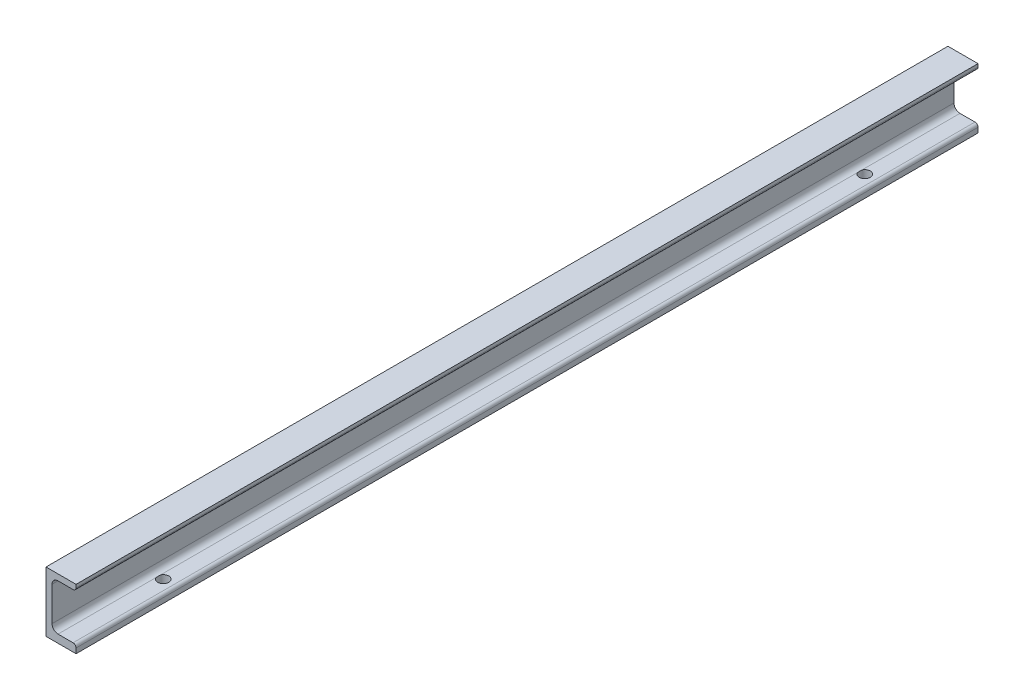
SolidWorks part; units mm, degrees
material "ASTM A36 Steel"
ref_plane "Front Plane" through (0, 0, 0) normal (0, 0, 1) x (1, 0, 0)
ref_plane "Top Plane" through (0, 0, 0) normal (0, 1, 0) x (1, 0, 0)
ref_plane "Right Plane" through (0, 0, 0) normal (1, 0, 0) x (0, 0, -1)
sketch "Sketch1" plane through (0, 0, 0) normal (0, 0, 1) x (1, 0, 0)
  line L0 (12, 24) -> (-3, 24)
  line L1 (-15, -30) -> (15, -30)
  line L2 (-15, -30) -> (-15, 30)
  line L3 (-15, 30) -> (15, 30)
  line L4 (15, -30) -> (15, -25)
  line L5 (-15, -30) -> (15, 30) construction
  line L6 (-15, 30) -> (15, -30) construction
  line L7 (-9, 18) -> (-9, -16)
  line L8 (-3, -22) -> (12, -22)
  line L9 (15, 27) -> (15, 30)
  arc A0 (-9, -16) -> (-3, -22) centre (-3, -16) ccw
  arc A1 (-3, 24) -> (-9, 18) centre (-3, 18) ccw
  arc A2 (12, -22) -> (15, -25) centre (12, -25) cw
  arc A3 (12, 24) -> (15, 27) centre (12, 27) ccw
  point P0 (0, 0)
  point P18 (15, 24)
  dimension "D5" = 6
  dimension "D6" = 3
  dimension "D1" = 60
  dimension "D2" = 30
  dimension "D3" = 6
  dimension "D4" = 6
  dimension "D7" = 8
extrude "Boss-Extrude1" add sketch "Sketch1" along normal mid plane 900
sketch "Sketch2" plane through (0, -22, 0) normal (0, 1, 0) x (1, 0, 0)
  line L0 (12, -450) -> (-3, -450) construction
  line L1 (15, -450) -> (15, 450) construction
  circle A0 centre (2, -350) radius 5.5
  dimension "D1" = 11
  dimension "D3" = 13
  dimension "D2" = 100
extrude "Cut-Extrude1" cut sketch "Sketch2" against normal blind 10
mirror "Mirror1" about plane through (0, 0, 0) normal (0, 0, 1) of "Cut-Extrude1"
